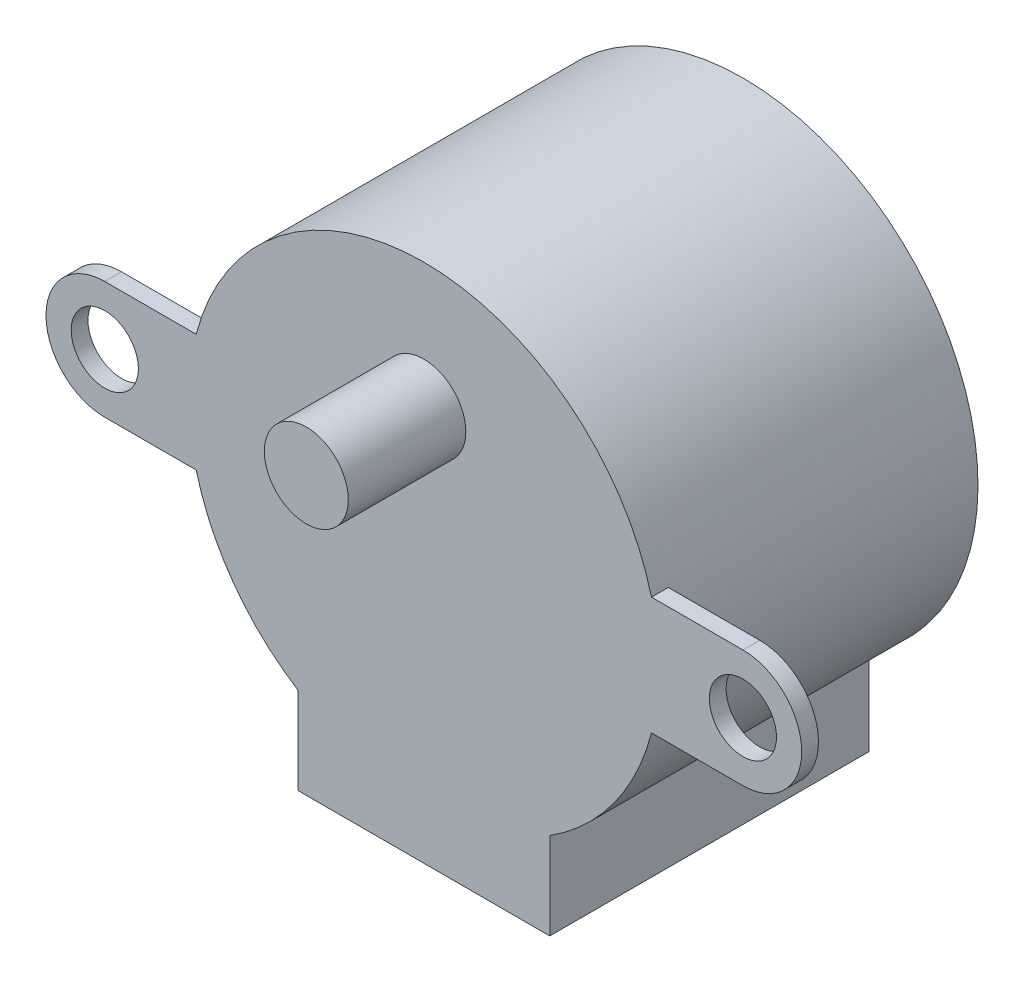
SolidWorks part; units mm, degrees
ref_plane "Plano frontal" through (0, 0, 0) normal (0, 0, 1) x (1, 0, 0)
ref_plane "Plano superior" through (0, 0, 0) normal (0, 1, 0) x (1, 0, 0)
ref_plane "Plano direito" through (0, 0, 0) normal (1, 0, 0) x (0, 0, -1)
sketch "Esboço1" plane through (0, 0, 0) normal (0, 0, 1) x (1, 0, 0)
  line L1 (19, 3.5) -> (13.5554, 3.5)
  line L2 (-7.5, -14) -> (-7.5, -11.8216)
  line L3 (13.5554, -3.5) -> (19, -3.5)
  line L4 (7.5, -14) -> (7.5, -17)
  line L5 (7.5, -17) -> (-7.5, -17)
  line L6 (7.5, -14) -> (7.5, -11.8216)
  line L7 (-7.5, -14) -> (-7.5, -17)
  line L8 (-13.5554, -3.5) -> (-19, -3.5)
  line L9 (-19, 3.5) -> (-13.5554, 3.5)
  arc A0 (13.5554, 3.5) -> (-13.5554, 3.5) centre (0, 0) ccw
  arc A1 (19, -3.5) -> (19, 3.5) centre (19, 0) ccw
  circle A2 centre (19, 0) radius 2
  arc A3 (7.5, -11.8216) -> (13.5554, -3.5) centre (0, 0) ccw
  circle A4 centre (-19, 0) radius 2
  arc A5 (-19, -3.5) -> (-19, 3.5) centre (-19, 0) cw
  arc A6 (-13.5554, -3.5) -> (-7.5, -11.8216) centre (0, 0) ccw
  point P16 (0, -17)
  point P18 (-7.5, -15.5)
extrude "Ressalto-extrusão1" add sketch "Esboço1" along normal blind 19
sketch "Esboço2" plane through (0, 0, 0) normal (0, 0, -1) x (-1, 0, 0)
  line L1 (13.5554, 3.5) -> (23.807, 3.5)
  line L3 (13.5554, -3.5) -> (23.807, -3.5)
  line L4 (23.807, 3.5) -> (23.807, -3.5)
  line L5 (-13.5554, 3.5) -> (-24.7605, 3.5)
  line L7 (-13.5554, -3.5) -> (-24.7605, -3.5)
  line L8 (-24.7605, 3.5) -> (-24.7605, -3.5)
  arc A0 (13.5554, -3.5) -> (13.5554, 3.5) centre (0, 0) ccw
  arc A1 (-13.5554, 3.5) -> (-13.5554, -3.5) centre (0, 0) ccw
extrude "Corte-extrusão1" cut sketch "Esboço2" against normal blind 18
sketch "Esboço3" plane through (0, 0, 19) normal (0, 0, 1) x (1, 0, 0)
  line L0 (-13.5554, 3.5) -> (13.5554, 3.5) construction
  line L1 (0, 3.5) -> (0, 6.5) construction
  circle A0 centre (0, 6.5) radius 2.5
extrude "Ressalto-extrusão2" add sketch "Esboço3" along normal blind 7
